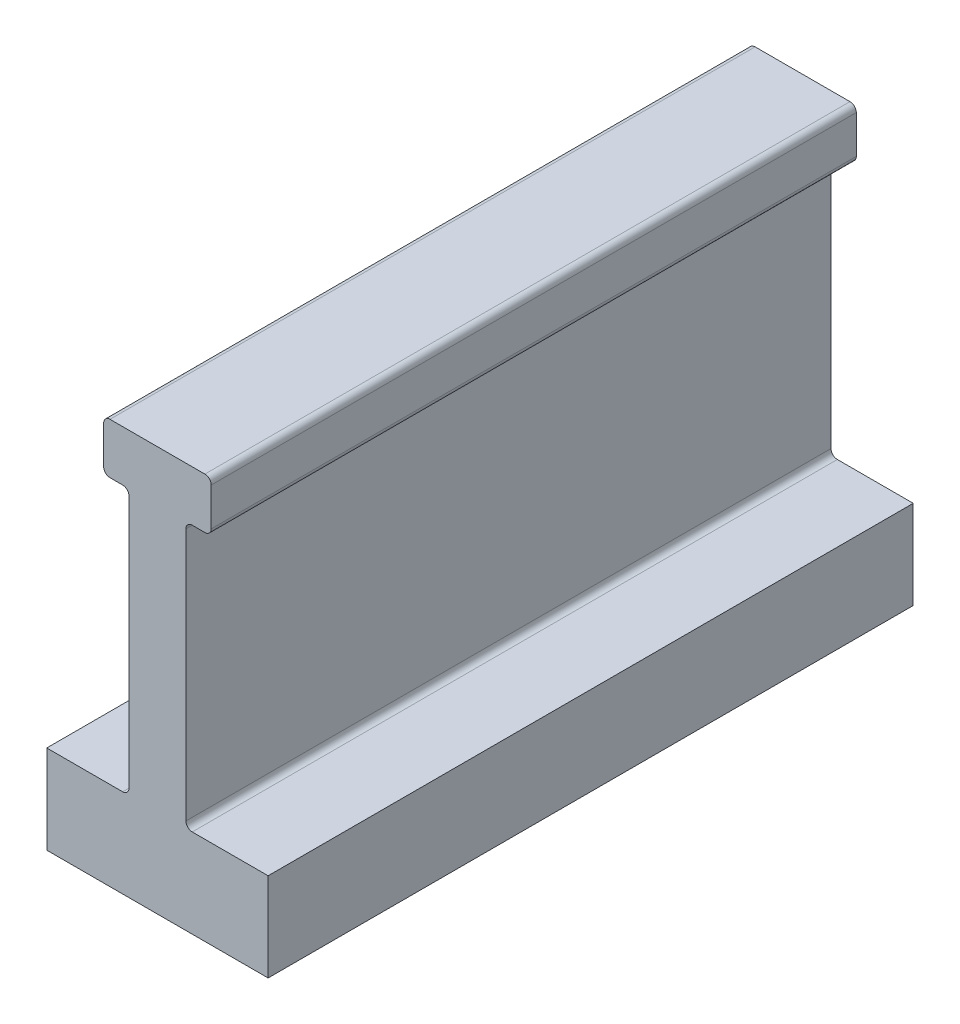
SolidWorks part; units mm, degrees
ref_plane "Front Plane" through (0, 0, 0) normal (0, 0, 1) x (1, 0, 0)
ref_plane "Top Plane" through (0, 0, 0) normal (0, 1, 0) x (1, 0, 0)
ref_plane "Right Plane" through (0, 0, 0) normal (1, 0, 0) x (0, 0, -1)
sketch "Sketch1" plane through (0, 0, 0) normal (0, 0, 1) x (1, 0, 0)
  line L0 (8.75, -14) -> (-8.75, -14)
  line L2 (-2.25, -6.5) -> (-2.25, 13.5)
  line L4 (2.25, -6.5) -> (2.25, 13.5)
  line L5 (-2.25, -14) -> (2.25, 14) construction
  line L6 (-2.25, 14) -> (2.25, -14) construction
  line L8 (2.75, 14) -> (3.75, 14)
  line L9 (-3.75, 18) -> (3.75, 18)
  line L10 (-4.25, 17.5) -> (-4.25, 14.5)
  line L11 (-3.75, 14) -> (-2.75, 14)
  line L12 (4.25, 17.5) -> (4.25, 14.5)
  line L13 (8.75, -14) -> (8.75, -7)
  line L14 (8.75, -7) -> (2.75, -7)
  line L15 (-8.75, -7) -> (-8.75, -14)
  line L17 (-2.75, -7) -> (-8.75, -7)
  arc A0 (-2.25, 13.5) -> (-2.75, 14) centre (-2.75, 13.5) ccw
  arc A1 (2.75, 14) -> (2.25, 13.5) centre (2.75, 13.5) ccw
  arc A2 (3.75, 18) -> (4.25, 17.5) centre (3.75, 17.5) cw
  arc A3 (-3.75, 18) -> (-4.25, 17.5) centre (-3.75, 17.5) ccw
  arc A4 (3.75, 14) -> (4.25, 14.5) centre (3.75, 14.5) ccw
  arc A5 (-4.25, 14.5) -> (-3.75, 14) centre (-3.75, 14.5) ccw
  arc A6 (2.25, -6.5) -> (2.75, -7) centre (2.75, -6.5) ccw
  arc A7 (-2.25, -6.5) -> (-2.75, -7) centre (-2.75, -6.5) cw
  point P0 (0, 0)
  point P14 (0, -14)
  point P25 (4.25, 18)
  point P28 (-4.25, 18)
  point P31 (4.25, 14)
  point P38 (-2.25, -7)
  dimension "D5" = 0.5
  dimension "D8" = 0.5
  dimension "D1" = 28
  dimension "D2" = 4.5
  dimension "D3" = 8.5
  dimension "D4" = 4
  dimension "D6" = 17.5
  dimension "D7" = 7
extrude "Boss-Extrude1" add sketch "Sketch1" along normal blind 51
